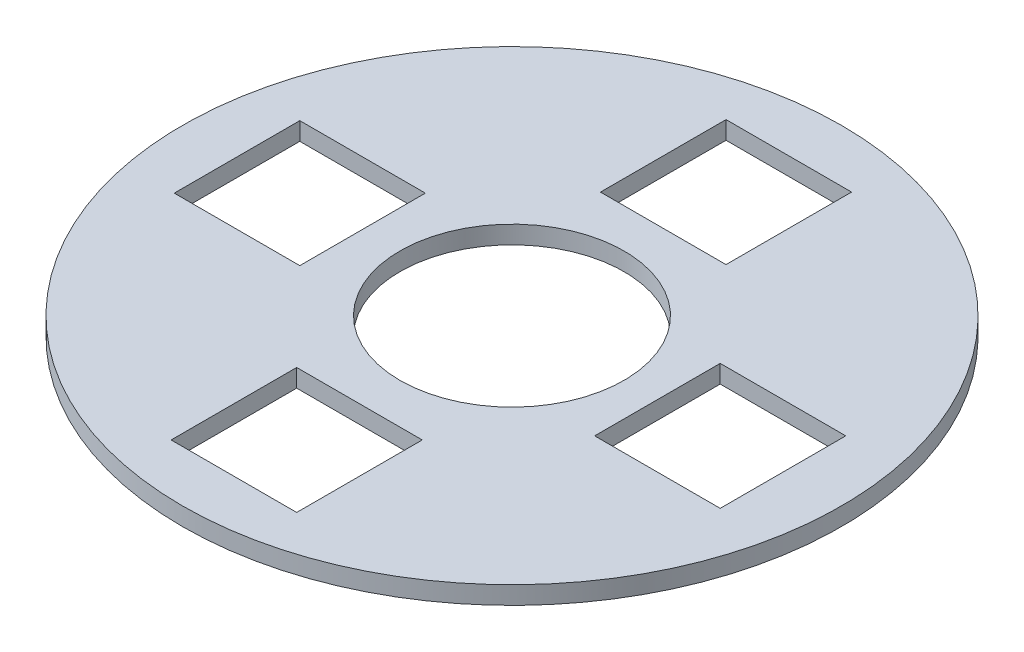
SolidWorks part; units mm, degrees
ref_plane "Front Plane" through (0, 0, 0) normal (0, 0, 1) x (1, 0, 0)
ref_plane "Top Plane" through (0, 0, 0) normal (0, 1, 0) x (1, 0, 0)
ref_plane "Right Plane" through (0, 0, 0) normal (1, 0, 0) x (0, 0, -1)
sketch "Sketch3" plane through (0, 0, 0) normal (0, 1, 0) x (1, 0, 0)
  circle A0 centre (0, 0) radius 36.75
  dimension "D1" = 73.5
extrude "Boss-Extrude1" add sketch "Sketch3" along normal blind 2 contours A0
sketch "Sketch4" plane through (0, 0, 0) normal (0, 1, 0) x (1, 0, 0)
  circle A0 centre (0, 0) radius 12.5
  dimension "D1" = 25
extrude "Cut-Extrude1" cut sketch "Sketch4" along normal through all
sketch "Sketch5" plane through (0, 2, 0) normal (0, 1, 0) x (1, 0, 0)
  line L10 (-30.6636, 7) -> (-30.6636, 0)
  line L11 (-30.6636, 0) -> (-30.6636, -7)
  line L15 (-30.6636, 7) -> (-16.6636, 7)
  line L16 (-16.6636, 7) -> (-16.6636, -7)
  line L17 (-16.6636, -7) -> (-30.6636, -7)
  dimension "D2" = 14
extrude "Cut-Extrude2" cut sketch "Sketch5" against normal through all contours L15 L16 L17 L11 L10
sketch "Sketch6" plane through (0, 2, 0) normal (0, 1, 0) x (1, 0, 0)
  line L0 (16.2181, 7) -> (16.2181, -7)
  line L10 (16.2181, 7) -> (30.2181, 7)
  line L11 (30.2181, 7) -> (30.2181, -7)
  line L12 (30.2181, -7) -> (16.2181, -7)
extrude "Cut-Extrude3" cut sketch "Sketch6" against normal through all
sketch "Sketch8" plane through (0, 0, 0) normal (0, 1, 0) x (1, 0, 0)
  line L5 (0, 30.8681) -> (-7, 30.8681)
  line L6 (0, 30.8681) -> (7, 30.8681)
  line L7 (-7, 30.8681) -> (-7, 16.8644)
  line L8 (-7, 16.8644) -> (7, 16.8644)
  line L9 (7, 16.8644) -> (7, 30.8681)
  line L13 (0, -31.0103) -> (7, -31.0103)
  line L14 (0, -31.0103) -> (-7, -31.0103)
  line L15 (-7, -31.0103) -> (-7, -17.0103)
  line L16 (-7, -17.0103) -> (7, -17.0103)
  line L17 (7, -17.0103) -> (7, -31.0103)
extrude "Cut-Extrude4" cut sketch "Sketch8" along normal through all
